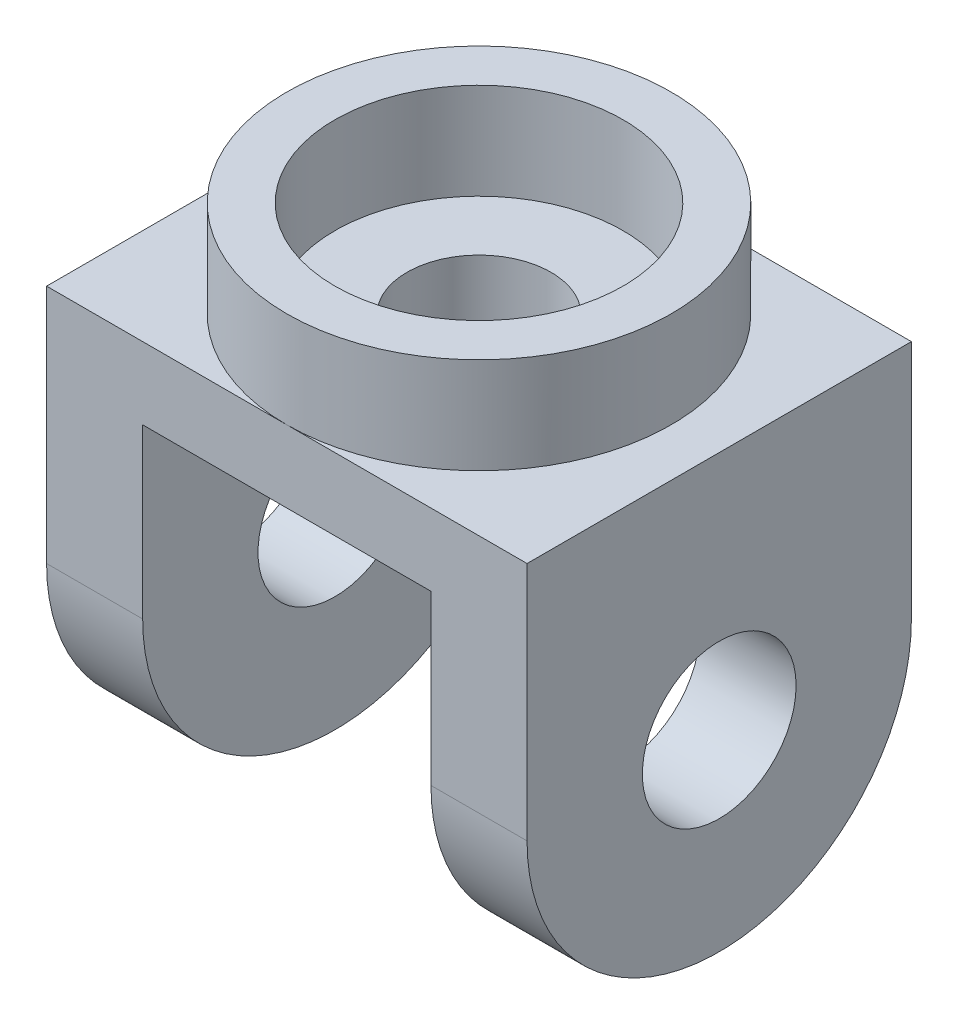
SolidWorks part; units mm, degrees
ref_plane "Front Plane" through (0, 0, 0) normal (0, 0, 1) x (1, 0, 0)
ref_plane "Top Plane" through (0, 0, 0) normal (0, 1, 0) x (1, 0, 0)
ref_plane "Right Plane" through (0, 0, 0) normal (1, 0, 0) x (0, 0, -1)
sketch "Sketch1" plane through (0, 0, 0) normal (0, 0, 1) x (1, 0, 0)
  line L0 (30, -25) -> (50, -25)
  line L1 (-50, -25) -> (-30, -25)
  line L2 (-50, -25) -> (-50, 25)
  line L3 (-50, 25) -> (50, 25)
  line L4 (50, -25) -> (50, 25)
  line L8 (-30, -25) -> (-30, 10)
  line L9 (-30, 10) -> (30, 10)
  line L10 (30, -25) -> (30, 10)
  point P0 (0, 0)
  point P6 (0, 0)
  dimension "D1" = 100
  dimension "D2" = 50
  dimension "D3" = 15
  dimension "D4" = 20
  dimension "D5" = 20
extrude "Boss-Extrude1" add sketch "Sketch1" against normal blind 80
sketch "Sketch2" plane through (50, 0, 0) normal (1, 0, 0) x (0, 0, -1)
  line L0 (80, -25) -> (0, -25) construction
  line L1 (0, -25) -> (80, -25)
  arc A0 (0, -25) -> (80, -25) centre (40, -25) ccw
extrude "Boss-Extrude2" add sketch "Sketch2" against normal blind 20
sketch "Sketch3" plane through (50, 0, 0) normal (1, 0, 0) x (0, 0, -1)
  circle A0 centre (40, -25) radius 16
  dimension "D1" = 32
extrude "Cut-Extrude1" cut sketch "Sketch3" against normal blind 20
ref_plane "Plane1" through (0, 0, 0) normal (1, 0, 0) x (0, 0, -1)
mirror "Mirror1" about plane through (0, 0, 0) normal (1, 0, 0) of "Cut-Extrude1", "Boss-Extrude2"
sketch "Sketch4" plane through (0, 25, 0) normal (0, 1, 0) x (1, 0, 0)
  circle A0 centre (0, 40) radius 40
  circle A1 centre (0, 40) radius 30
  dimension "D1" = 80
  dimension "D2" = 60
extrude "Boss-Extrude3" add sketch "Sketch4" along normal blind 20
sketch "Sketch5" plane through (0, 25, 0) normal (0, 1, 0) x (1, 0, 0)
  circle A0 centre (0, 40) radius 15
  dimension "D1" = 30
extrude "Cut-Extrude2" cut sketch "Sketch5" against normal through all
